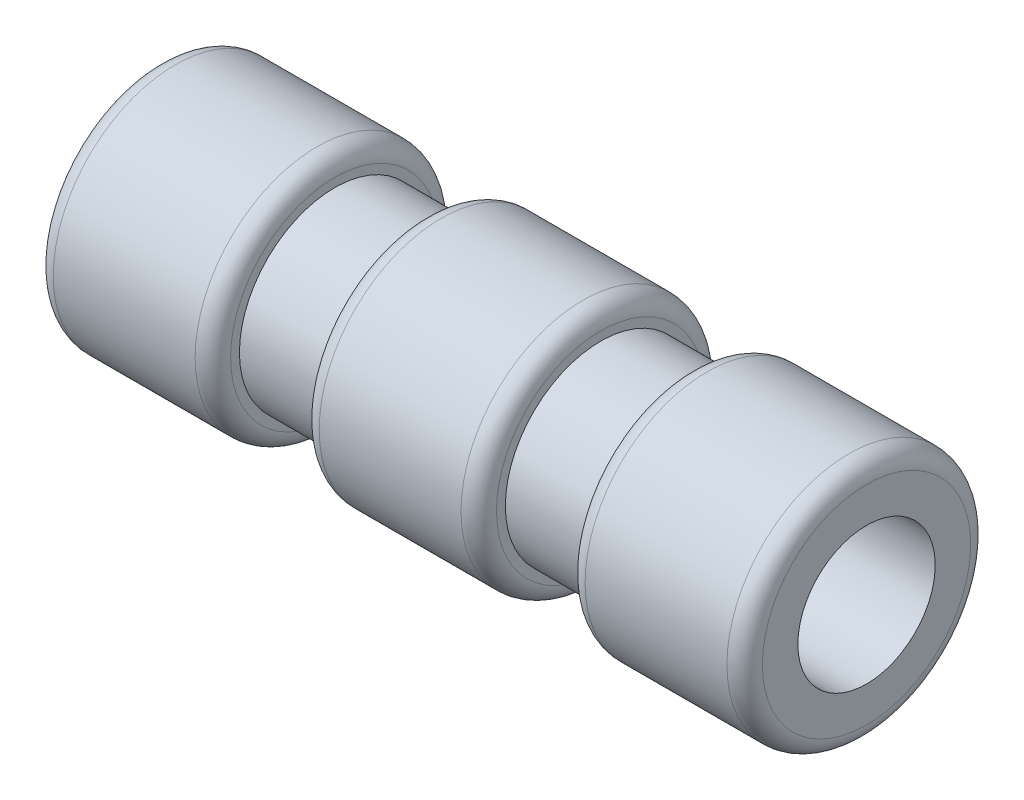
SolidWorks part; units mm, degrees
ref_plane "Front Plane" through (0, 0, 0) normal (0, 0, 1) x (1, 0, 0)
ref_plane "Top Plane" through (0, 0, 0) normal (0, 1, 0) x (1, 0, 0)
ref_plane "Right Plane" through (0, 0, 0) normal (1, 0, 0) x (0, 0, -1)
sketch "Sketch1" plane through (0, 0, 0) normal (0, 1, 0) x (1, 0, 0)
  line L0 (-168.8544, 0) -> (168.8544, 0) construction
  line L1 (0, 0) -> (0, 19.3761) construction
  line L2 (100, 19.3761) -> (-100, 19.3761)
  line L3 (-100, 19.3761) -> (-100, 34.3761)
  line L4 (-100, 34.3761) -> (-50, 34.3761)
  line L5 (-50, 34.3761) -> (-50, 26.8761)
  line L6 (-50, 26.8761) -> (-25, 26.8761)
  line L7 (-25, 26.8761) -> (-25, 34.3761)
  line L8 (-25, 34.3761) -> (25, 34.3761)
  line L9 (25, 26.8761) -> (25, 34.3761)
  line L10 (50, 26.8761) -> (25, 26.8761)
  line L11 (50, 34.3761) -> (50, 26.8761)
  line L12 (100, 34.3761) -> (50, 34.3761)
  line L13 (100, 19.3761) -> (100, 34.3761)
  point P13 (0, 34.3761)
  dimension "D1" = 15
  dimension "D2" = 50
  dimension "D3" = 7.5
  dimension "D4" = 100
  dimension "D5" = 25
revolve "Revolve1" add sketch "Sketch1" angle 360 about L0
fillet "Fillet1" radius 5 6 edges at (-50, 0, 34.3761) (-100, 0, 34.3761) (-25, 0, 34.3761) (25, 0, 34.3761) (50, 0, 34.3761) (100, 0, 34.3761)
